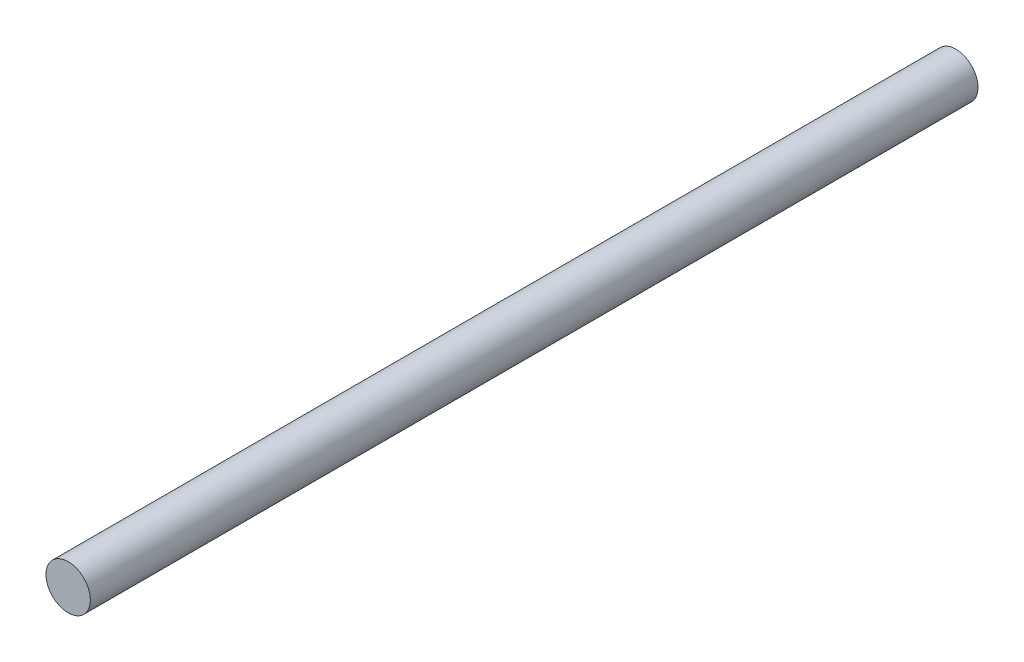
SolidWorks part; units mm, degrees
ref_plane "Ön Düzlem" through (0, 0, 0) normal (0, 0, 1) x (1, 0, 0)
ref_plane "Üst Düzlem" through (0, 0, 0) normal (0, 1, 0) x (1, 0, 0)
ref_plane "Sağ Düzlem" through (0, 0, 0) normal (1, 0, 0) x (0, 0, -1)
sketch "Çizim1" plane through (0, 0, 0) normal (0, 0, 1) x (1, 0, 0)
  circle A0 centre (0, 0) radius 7.5
  dimension "D1" = 15
extrude "Yükseklik-Ekstrüzyon1" add sketch "Çizim1" along normal blind 300
